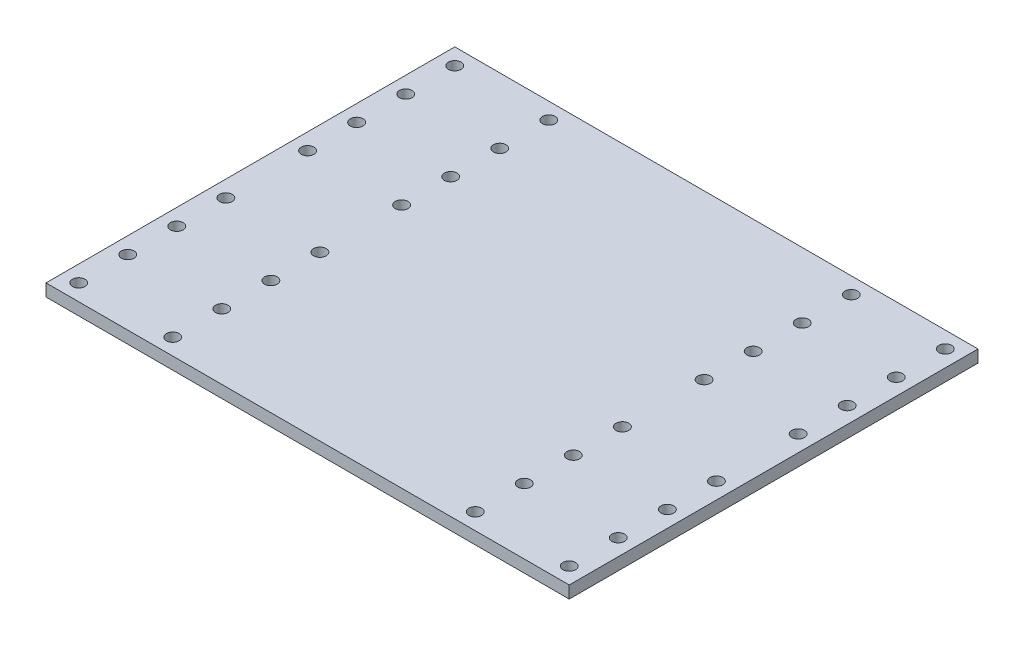
SolidWorks part; units mm, degrees
material "Thornel Mat VMA"
ref_plane "前视基准面" through (0, 0, 0) normal (0, 0, 1) x (1, 0, 0)
ref_plane "上视基准面" through (0, 0, 0) normal (0, 1, 0) x (1, 0, 0)
ref_plane "右视基准面" through (0, 0, 0) normal (1, 0, 0) x (0, 0, -1)
sketch "草图1" plane through (0, 0, 0) normal (0, 1, 0) x (1, 0, 0)
  line L1 (-50, 40) -> (50, 40) construction
  line L2 (-50, 40) -> (-50, -40) construction
  line L3 (-50, -40) -> (50, -40) construction
  line L4 (50, 40) -> (50, -40) construction
  line L5 (-50, 40) -> (50, -40) construction
  line L6 (-50, -40) -> (50, 40) construction
  line L10 (-61.5, -34) -> (-61.5, -46) construction
  line L15 (-63, -46) -> (-37, -46) construction
  line L16 (-63, -46) -> (-63, -34) construction
  line L21 (-63, -34) -> (-37, -34) construction
  line L22 (-37, -46) -> (-37, -34) construction
  line L27 (-63, -46) -> (-37, -34) construction
  line L28 (-63, -34) -> (-37, -46) construction
  line L29 (64, 50) -> (-64, 50)
  line L30 (64, 50) -> (64, -50)
  line L31 (64, -50) -> (-64, -50)
  line L32 (-64, 50) -> (-64, -50)
  line L33 (64, 50) -> (-64, -50) construction
  line L34 (64, -50) -> (-64, 50) construction
  line L39 (-60, -34) -> (-60, -46) construction
  line L40 (-58.5, -34) -> (-58.5, -46) construction
  line L41 (-57, -34) -> (-57, -46) construction
  line L42 (-50, 0) -> (0, 0) construction
  line L43 (0, 0) -> (0, -40) construction
  circle A0 centre (-60, -46) radius 1.55
  circle A1 centre (-37, -46) radius 1.55
  circle A2 centre (-37, -34) radius 1.55
  circle A4 centre (-60, -34) radius 1.55
  circle A5 centre (-37, -10) radius 1.55
  circle A6 centre (-37, -22) radius 1.55
  circle A7 centre (-60, -10) radius 1.55
  circle A8 centre (-60, -22) radius 1.55
  circle A9 centre (60, -34) radius 1.55
  circle A10 centre (60, -46) radius 1.55
  circle A11 centre (37, -46) radius 1.55
  circle A12 centre (37, -34) radius 1.55
  circle A13 centre (60, -22) radius 1.55
  circle A14 centre (37, -22) radius 1.55
  circle A15 centre (37, -10) radius 1.55
  circle A16 centre (60, -10) radius 1.55
  circle A17 centre (60, 10) radius 1.55
  circle A18 centre (37, 10) radius 1.55
  circle A19 centre (37, 22) radius 1.55
  circle A20 centre (60, 22) radius 1.55
  circle A21 centre (60, 34) radius 1.55
  circle A22 centre (60, 46) radius 1.55
  circle A23 centre (37, 34) radius 1.55
  circle A24 centre (37, 46) radius 1.55
  circle A25 centre (-60, 46) radius 1.55
  circle A26 centre (-37, 46) radius 1.55
  circle A27 centre (-37, 34) radius 1.55
  circle A28 centre (-60, 34) radius 1.55
  circle A29 centre (-60, 22) radius 1.55
  circle A30 centre (-37, 22) radius 1.55
  circle A31 centre (-37, 10) radius 1.55
  circle A32 centre (-60, 10) radius 1.55
  point P0 (0, 0)
  point P6 (0, 0)
  point P46 (58.5, -34)
  dimension "D11" = 3.1
  dimension "D1" = 100
  dimension "D2" = 80
  dimension "D4" = 1.5
  dimension "D5" = 1.5
  dimension "D3" = 1
  dimension "D6" = 1.5
  dimension "D7" = 1.5
  dimension "D8" = 10
  dimension "D9" = 12
  dimension "D10" = 4
  dimension "D12" = 2
extrude "凸台-拉伸1" add sketch "草图1" along normal blind 3
